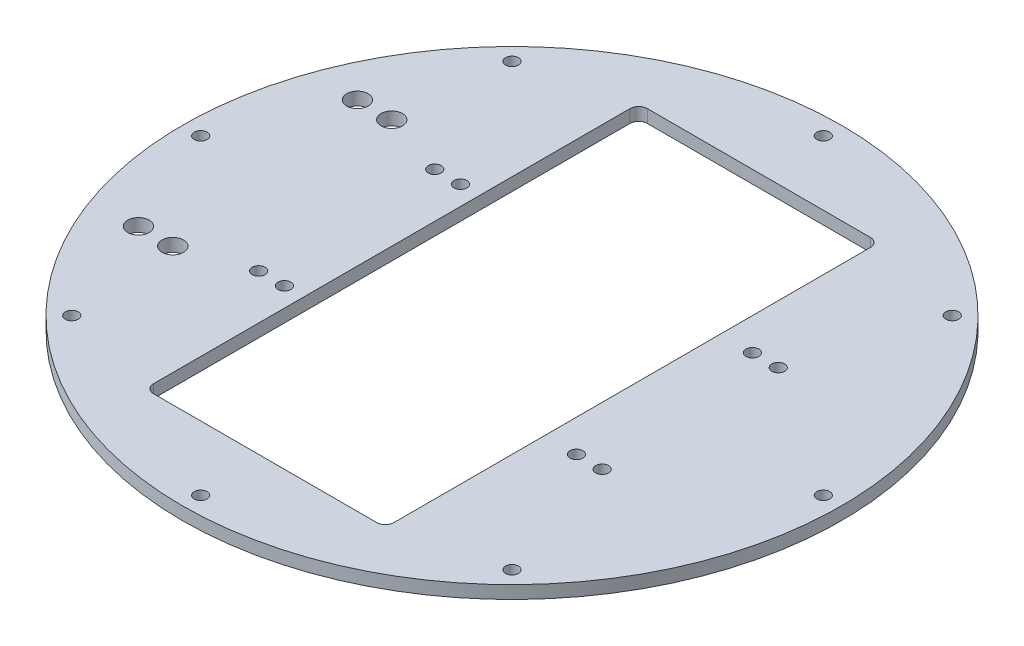
SolidWorks part; units mm, degrees
material "碳板"
ref_plane "前视基准面" through (0, 0, 0) normal (0, 0, 1) x (1, 0, 0)
ref_plane "上视基准面" through (0, 0, 0) normal (0, 1, 0) x (1, 0, 0)
ref_plane "右视基准面" through (0, 0, 0) normal (1, 0, 0) x (0, 0, -1)
sketch "草图1" plane through (0, 0, 0) normal (0, 1, 0) x (1, 0, 0)
  line L0 (0, 60.9717) -> (0, -61.944) construction
  line L5 (28, 0) -> (-36.6539, 0) construction
  line L13 (-28, 57.5) -> (28, 57.5)
  line L14 (-28, 57.5) -> (-28, -57.5)
  line L15 (-28, -57.5) -> (28, -57.5)
  line L16 (28, 57.5) -> (28, -57.5)
  line L17 (-28, 57.5) -> (28, -57.5) construction
  line L18 (-28, -57.5) -> (28, 57.5) construction
  circle A0 centre (0, 0) radius 76.75
  circle A1 centre (0, 0) radius 72.5 construction
  circle A2 centre (0, 72.5) radius 1.5
  circle A3 centre (51.2652, 51.2652) radius 1.5
  circle A4 centre (72.5, 0) radius 1.5
  circle A5 centre (51.2652, -51.2652) radius 1.5
  circle A6 centre (0, -72.5) radius 1.5
  circle A7 centre (-51.2652, -51.2652) radius 1.5
  circle A8 centre (-72.5, 0) radius 1.5
  circle A9 centre (-51.2652, 51.2652) radius 1.5
  circle A10 centre (-32.5, -20.5) radius 1.5 construction
  circle A12 centre (-32.5, -20.5) radius 1.5
  circle A14 centre (-38.5, -20.5) radius 1.5 construction
  circle A16 centre (-38.5, -20.5) radius 1.5
  circle A18 centre (-38.5, 20.5) radius 1.5 construction
  circle A20 centre (-38.5, 20.5) radius 1.5
  circle A29 centre (-53.5, 25.5) radius 2.5
  circle A31 centre (-61.5, 25.5) radius 2.5
  circle A35 centre (-53.5, -25.5) radius 2.5
  circle A37 centre (-61.5, -25.5) radius 2.5
  circle A39 centre (-32.5, 20.5) radius 1.5 construction
  circle A41 centre (-32.5, 20.5) radius 1.5
  circle A46 centre (35.5, 20.5) radius 1.5 construction
  circle A47 centre (35.5, 20.5) radius 1.5
  circle A48 centre (41.5, 20.5) radius 1.5 construction
  circle A49 centre (41.5, 20.5) radius 1.5
  circle A50 centre (35.5, -20.5) radius 1.5 construction
  circle A51 centre (35.5, -20.5) radius 1.5
  circle A52 centre (41.5, -20.5) radius 1.5 construction
  circle A53 centre (41.5, -20.5) radius 1.5
  point P7 (0, 0)
  point P22 (0, 0)
  dimension "D1" = 153.5
  dimension "D2" = 145
  dimension "D3" = 3
  dimension "D6" = 56
  dimension "D8" = 61.5
  dimension "D7" = 53.5
  dimension "D9" = 5
  dimension "D5" = 115
  dimension "D10" = 51
  dimension "D4" = 8
extrude "凸台-拉伸1" add sketch "草图1" along normal blind 3
fillet "圆角1" radius 2 4 edges at (-28, 1.5, 57.5) (28, 1.5, 57.5) (28, 1.5, -57.5) (-28, 1.5, -57.5)
